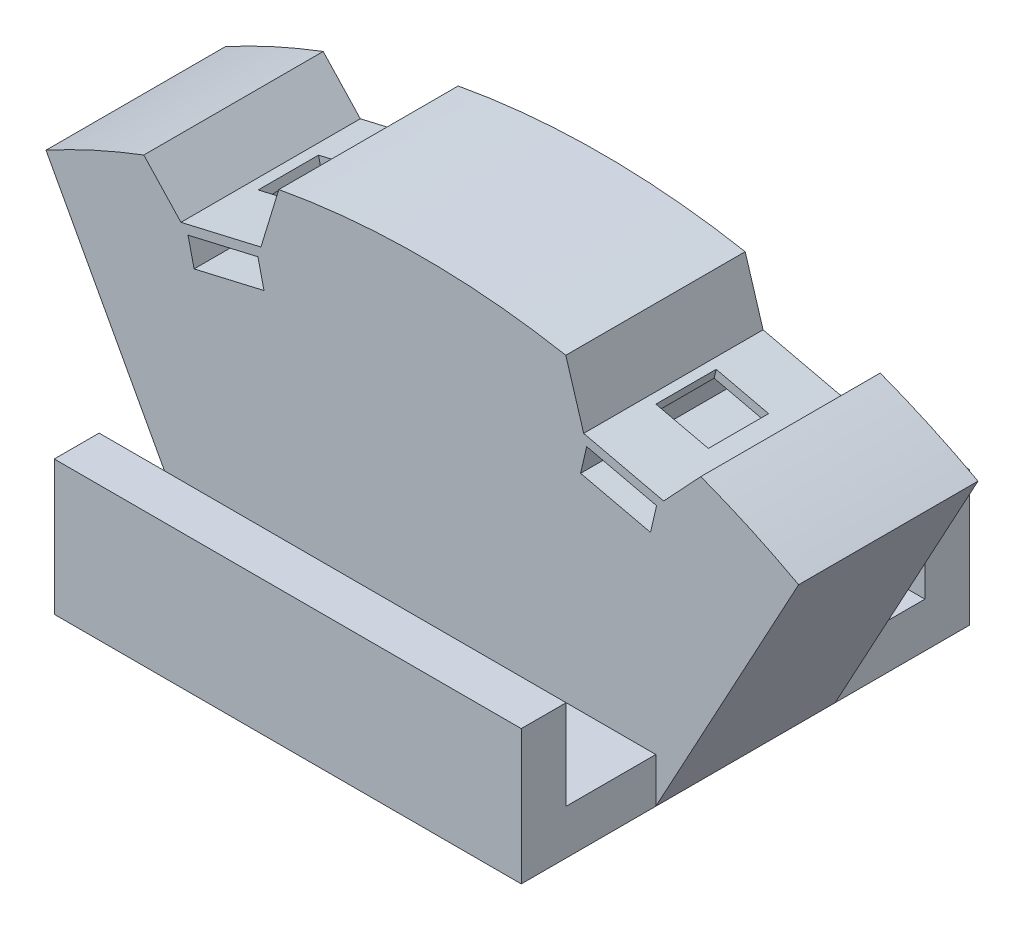
SolidWorks part; units mm, degrees
ref_plane "Front Plane" through (0, 0, 0) normal (0, 0, 1) x (1, 0, 0)
ref_plane "Top Plane" through (0, 0, 0) normal (0, 1, 0) x (1, 0, 0)
ref_plane "Right Plane" through (0, 0, 0) normal (1, 0, 0) x (0, 0, -1)
ref_plane "Plane1"
sketch "Sketch1" plane through (0, 0, 0) normal (0, 0, 1) x (1, 0, 0)
  line L0 (-46.8353, 30.48) -> (46.8353, 30.48)
  arc A0 (46.8353, 30.48) -> (0, 55.88) centre (0, 0) ccw
  arc A1 (0, 55.88) -> (-46.8353, 30.48) centre (0, 0) ccw
extrude "Extrusion1" add sketch "Sketch1" against normal blind 12.7
ref_plane "Plane2"
sketch "Sketch2" plane through (0, 0, 0) normal (0, 0, 1) x (1, 0, 0)
  line L0 (-10.16, 54.9486) -> (-13.6298, 58.659)
  line L1 (-13.6298, 58.659) -> (-18.578, 57.5092)
  line L2 (-18.578, 57.5092) -> (-20.0564, 52.6491)
  line L3 (-20.0564, 52.6491) -> (-17.0874, 49.4743)
  line L4 (-17.0874, 49.4743) -> (-11.425, 50.79)
  line L5 (-11.425, 50.79) -> (-10.16, 54.9486)
  line L6 (10.16, 54.9486) -> (11.425, 50.79)
  line L7 (11.425, 50.79) -> (17.0874, 49.4743)
  line L8 (17.0874, 49.4743) -> (20.0564, 52.6491)
  line L9 (20.0564, 52.6491) -> (18.578, 57.5092)
  line L10 (18.578, 57.5092) -> (13.6298, 58.659)
  line L11 (13.6298, 58.659) -> (10.16, 54.9486)
  line L12 (-46.8353, 30.48) -> (-0.0003, 0.0002)
  line L13 (-0.0002, 0.0003) -> (-26.6416, 49.1203)
  line L14 (26.6416, 49.1203) -> (0.0002, 0.0003)
  line L15 (0.0003, 0.0002) -> (46.8353, 30.48)
  line L16 (16.5866, 48.9387) -> (11.6384, 50.0885)
  line L17 (11.6384, 50.0885) -> (11.2073, 48.2333)
  line L18 (11.2073, 48.2333) -> (16.1555, 47.0836)
  line L19 (16.1555, 47.0836) -> (16.5866, 48.9387)
  line L20 (-11.6384, 50.0885) -> (-16.5866, 48.9387)
  line L21 (-16.5866, 48.9387) -> (-16.1554, 47.0832)
  line L22 (-16.1554, 47.0832) -> (-11.2072, 48.2329)
  line L23 (-11.2072, 48.2329) -> (-11.6384, 50.0885)
  arc A0 (-26.6416, 49.1203) -> (-46.8353, 30.48) centre (0, 0) ccw
  arc A1 (46.8353, 30.48) -> (26.6416, 49.1203) centre (0, 0) ccw
  arc A2 (-0.0003, 0.0002) -> (-0.0002, 0.0003) centre (-0.0003, 0.0003) ccw
  arc A3 (0.0002, 0.0003) -> (0.0003, 0.0002) centre (0.0003, 0.0003) ccw
  dimension "D1" = 0.0001
  dimension "D2" = 0.0001
extrude "Extrusion2" cut sketch "Sketch2" against normal blind 12.7 contours L4 L5 L0 L1 L2 L3 | L10 L11 L6 L7 L8 L9 | L12 A2 L13 A0 | L14 A3 L15 A1 | L18 L19 L16 L17 | L22 L23 L20 L21
sketch "Sketch3" plane through (-11.7821, 50.707, 0) normal (-0.2263, 0.9741, 0) x (-0.9741, -0.2263, 0)
  line L0 (4.445, -8.763) -> (4.445, -4.4937)
  line L1 (4.445, -4.4937) -> (0.635, -4.4937)
  line L2 (0.635, -4.4937) -> (0.635, -8.763)
  line L3 (0.635, -8.763) -> (4.445, -8.763)
  dimension "D1" = 5.5022
  dimension "D2" = 3.81
  dimension "D3" = 9.3205
extrude "Extrusion3" cut sketch "Sketch3" against normal up to next
sketch "Sketch4" plane through (11.7821, 50.707, 0) normal (0.2263, 0.9741, 0) x (-0.9741, 0.2263, 0)
  line L0 (-0.2684, -8.763) -> (-0.2684, -4.4958)
  line L1 (-0.2684, -4.4958) -> (-4.0784, -4.4958)
  line L2 (-4.0784, -4.4958) -> (-4.0784, -8.763)
  line L3 (-4.0784, -8.763) -> (-0.2684, -8.763)
  dimension "D1" = 3.81
  dimension "D2" = 9.202
  dimension "D3" = 4.5404
  dimension "D4" = 4.2672
extrude "Extrusion4" cut sketch "Sketch4" against normal up to next
ref_plane "Plane3"
sketch "Sketch5" plane through (0, 0, -12.7) normal (0, 0, -1) x (-1, 0, 0)
  line L0 (-16.5316, 30.48) -> (16.5316, 30.48)
  line L1 (16.5316, 30.48) -> (16.5316, 33.655)
  line L2 (16.5316, 33.655) -> (-16.5316, 33.655)
  line L3 (-16.5316, 33.655) -> (-16.5316, 30.48)
  dimension "D1" = 3.175
extrude "Extrusion5" add sketch "Sketch5" along normal blind 9.525
sketch "Sketch6" plane through (0, 33.655, 0) normal (0, 1, 0) x (-1, 0, 0)
  line L0 (-16.5316, -22.225) -> (16.5316, -22.225)
  line L1 (16.5316, -22.225) -> (16.5316, -19.05)
  line L2 (16.5316, -19.05) -> (-16.5316, -19.05)
  line L3 (-16.5316, -19.05) -> (-16.5316, -22.225)
  dimension "D1" = 3.175
extrude "Extrusion6" add sketch "Sketch6" along normal blind 6.35
ref_plane "Plane4"
sketch "Sketch7" plane through (0, 0, 0) normal (0, 0, 1) x (1, 0, 0)
  line L0 (16.5316, 30.48) -> (16.5316, 33.655)
  line L1 (16.5316, 33.655) -> (-16.5316, 33.655)
  line L2 (-16.5316, 33.655) -> (-16.5316, 30.48)
  line L3 (-16.5316, 30.48) -> (16.5316, 30.48)
  dimension "D1" = 3.175
extrude "Extrusion7" add sketch "Sketch7" along normal blind 9.525
sketch "Sketch8" plane through (0, 33.655, 0) normal (0, 1, 0) x (-1, 0, 0)
  line L0 (16.5316, 9.525) -> (-16.5316, 9.525)
  line L1 (-16.5316, 9.525) -> (-16.5316, 6.35)
  line L2 (-16.5316, 6.35) -> (16.5316, 6.35)
  line L3 (16.5316, 6.35) -> (16.5316, 9.525)
  dimension "D1" = 3.175
extrude "Extrusion8" add sketch "Sketch8" along normal blind 6.35
